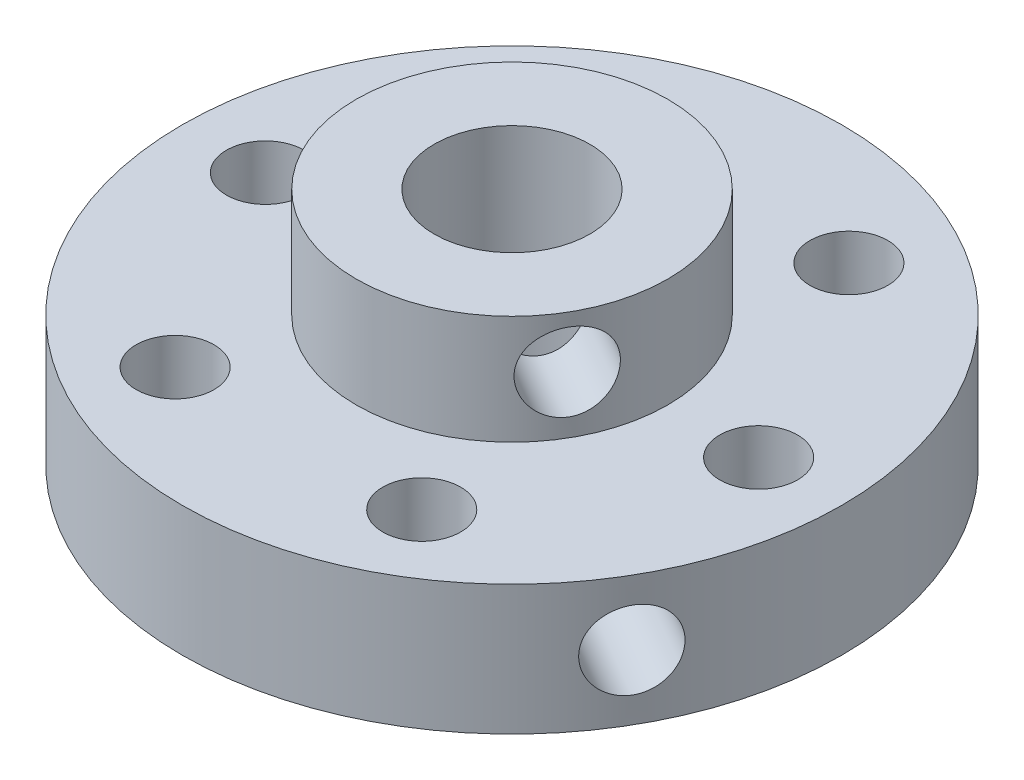
SolidWorks part; units mm, degrees
ref_plane "Front Plane" through (0, 0, 0) normal (0, 0, 1) x (1, 0, 0)
ref_plane "Top Plane" through (0, 0, 0) normal (0, 1, 0) x (1, 0, 0)
ref_plane "Right Plane" through (0, 0, 0) normal (1, 0, 0) x (0, 0, -1)
sketch "Sketch1" plane through (0, 0, 0) normal (0, 1, 0) x (1, 0, 0)
  circle A0 centre (0, 0) radius 12.7
  dimension "D1" = 25.4
extrude "Boss-Extrude1" add sketch "Sketch1" along normal blind 5
sketch "Sketch2" plane through (0, 5, 0) normal (0, 1, 0) x (1, 0, 0)
  circle A0 centre (0, 0) radius 6
  circle A1 centre (0, 0) radius 12.7 construction
  dimension "D1" = 12
extrude "Boss-Extrude2" add sketch "Sketch2" along normal blind 4.2
sketch "Sketch3" plane through (0, 9.2, 0) normal (0, 1, 0) x (1, 0, 0)
  circle A0 centre (0, 0) radius 3
  circle A1 centre (0, 0) radius 9.5 construction
  circle A2 centre (-9.5, 0) radius 1.5
  circle A3 centre (-4.75, 8.2272) radius 1.5
  circle A4 centre (4.75, 8.2272) radius 1.5
  circle A5 centre (9.5, 0) radius 1.5
  circle A6 centre (4.75, -8.2272) radius 1.5
  circle A7 centre (-4.75, -8.2272) radius 1.5
  point P19 (0, 0)
  dimension "D1" = 6
  dimension "D2" = 19
  dimension "D3" = 3
  dimension "D4" = 6
extrude "Cut-Extrude1" cut sketch "Sketch3" against normal blind 14.2
sketch "Sketch4" plane through (0, 5, 0) normal (0, 1, 0) x (1, 0, 0)
  line L0 (4.75, -8.2272) -> (9.5, 0) construction
  line L1 (0, 0) -> (7.125, -4.1136) construction
ref_plane "Plane1" through (7.125, 0, 4.1136) normal (0.866, 0, 0.5) x (0.5, 0, -0.866)
sketch "Sketch5" plane through (7.125, 0, 4.1136) normal (0.866, 0, 0.5) x (0.5, 0, -0.866)
  line L0 (-12.7, 0) -> (12.7, 0) construction
  line L1 (0, -0.2092) -> (0, 10.5629) construction
  line L2 (6, 5) -> (-6, 5) construction
  circle A0 centre (0, 2.5) radius 1.5
  circle A1 centre (0, 7.2) radius 1.5
  dimension "D1" = 3
  dimension "D3" = 3
  dimension "D2" = 2.5
  dimension "D4" = 2.2
extrude "Cut-Extrude2" cut sketch "Sketch5" against normal mid plane 14.2
